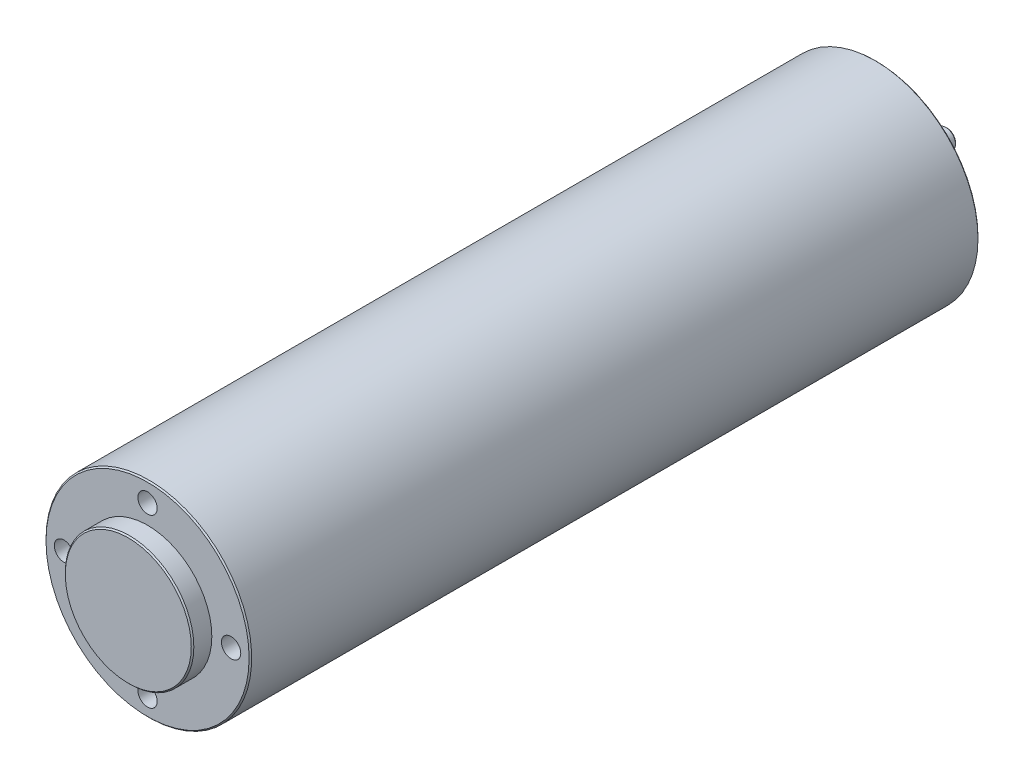
SolidWorks part; units mm, degrees
ref_plane "Alzado" through (0, 0, 0) normal (0, 0, 1) x (1, 0, 0)
ref_plane "Planta" through (0, 0, 0) normal (0, 1, 0) x (1, 0, 0)
ref_plane "Vista lateral" through (0, 0, 0) normal (1, 0, 0) x (0, 0, -1)
sketch "Croquis1" plane through (0, 0, 0) normal (0, 0, 1) x (1, 0, 0)
  circle A0 centre (0, 0) radius 16
extrude "Saliente-Extruir1" add sketch "Croquis1" along normal blind 113.4 contours A0
sketch "Croquis2" plane through (0, 0, 113.4) normal (0, 0, 1) x (1, 0, 0)
  circle A0 centre (0, 0) radius 10
extrude "Saliente-Extruir2" add sketch "Croquis2" along normal blind 3
sketch "Croquis3" plane through (0, 0, 0) normal (0, 0, -1) x (-1, 0, 0)
  circle A0 centre (0, 0) radius 6
extrude "Saliente-Extruir3" add sketch "Croquis3" along normal blind 2
sketch "Croquis4" plane through (0, 0, -2) normal (0, 0, -1) x (-1, 0, 0)
  circle A0 centre (0, 0) radius 1.5
extrude "Saliente-Extruir4" add sketch "Croquis4" along normal blind 9
chamfer "Chaflán1" distance 0.2 angle 45 5 edges at (10, 0, 116.4) (16, 0, 113.4) (16, 0, 0) (-6, 0, -2) (-1.5, 0, -11)
sketch "Croquis5" plane through (0, 0, 113.4) normal (0, 0, 1) x (1, 0, 0)
  line L0 (0, 0) -> (13, 0) construction
  line L1 (13, 0) -> (-13, 0) construction
  line L2 (-13, 0) -> (0, 0) construction
  line L3 (0, 0) -> (0, 13) construction
  line L4 (0, 13) -> (0, -13) construction
  circle A0 centre (0, 13) radius 1.5
  circle A1 centre (13, 0) radius 1.5
  circle A2 centre (0, -13) radius 1.5
  circle A3 centre (-13, 0) radius 1.5
extrude "Cortar-Extruir1" cut sketch "Croquis5" against normal blind 4
